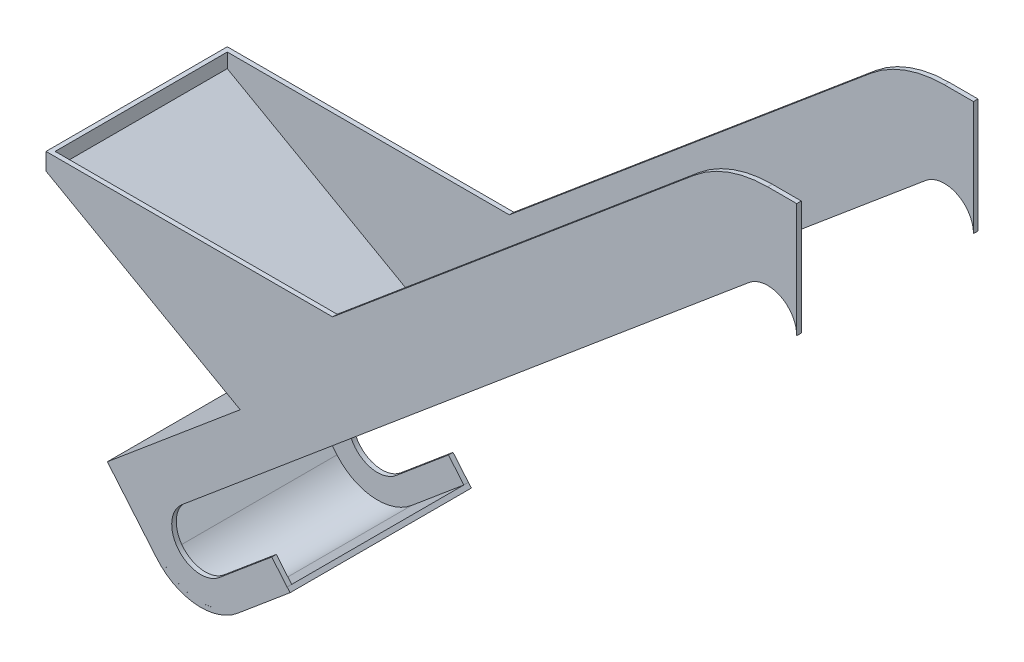
SolidWorks part; units mm, degrees
ref_plane "前视基准面" through (0, 0, 0) normal (0, 0, 1) x (1, 0, 0)
ref_plane "上视基准面" through (0, 0, 0) normal (0, 1, 0) x (1, 0, 0)
ref_plane "右视基准面" through (0, 0, 0) normal (1, 0, 0) x (0, 0, -1)
sketch "草图4" plane through (0, 0, 0) normal (0, 0, 1) x (1, 0, 0)
  line L0 (420.9878, 562.8861) -> (471.9878, 562.8861)
  line L1 (-659.0341, -373.4463) -> (-501.8251, -241.5173)
  line L2 (-659.0341, -373.4463) -> (-730.1522, -433.1283)
  line L3 (-730.1522, -433.1283) -> (-645.9414, -533.4754)
  line L4 (471.9878, 361.8861) -> (471.9878, 562.8861)
  line L7 (-542.039, -512.8599) -> (-450.118, -435.7202)
  line L8 (-423.1191, -467.8926) -> (-515.0187, -545.0143)
  line L9 (-659.0341, -373.4463) -> (336.777, 462.2332) construction
  line L10 (-607.6077, -434.727) -> (388.2035, 400.9525)
  line L11 (-450.118, -435.7202) -> (-423.1191, -467.8926)
  line L12 (-343.1983, -17.0157) -> (291.7789, 515.8538)
  line L14 (-846.6236, -17.0157) -> (-846.6236, -47.0157)
  line L15 (-846.6236, -17.0157) -> (-343.1983, -17.0157)
  line L16 (-846.6236, -47.0157) -> (-501.8251, -241.5173)
  arc A3 (-542.039, -512.8599) -> (-607.6077, -434.727) centre (-574.8233, -473.7934) cw
  arc A4 (388.2035, 400.9525) -> (471.9878, 361.8861) centre (420.9878, 361.8861) cw
  arc A5 (-515.0187, -545.0143) -> (-645.9414, -533.4754) centre (-574.7026, -473.6922) cw
  arc A7 (291.7789, 515.8538) -> (420.9878, 562.8861) centre (420.9878, 361.8861) cw
  point P33 (471.9878, 562.8861)
  dimension "D3" = 42
  dimension "D1" = 150
  dimension "D2" = 80
extrude "凸台-拉伸1" add sketch "草图4" along normal mid plane 8
pattern_linear "阵列(线性)1" count 2 spacing 310.4 along (0, 0, 1) of bodies 101
sketch "草图7" plane through (-224.4912, -397.962, 0) normal (-0.4913, -0.871, 0) x (0.871, -0.4913, 0)
  line L4 (-714.2913, 314.4) -> (-318.4164, 314.4)
  line L6 (-318.4164, 314.4) -> (-318.4164, -4)
  line L8 (-714.2913, 314.4) -> (-714.2913, -4)
  line L9 (-714.2913, -4) -> (-318.4164, -4)
extrude "凸台-拉伸2" add sketch "草图7" against normal blind 8
sketch "草图8" plane through (-846.6236, 0, 0) normal (-1, 0, 0) x (0, 0, 1)
  line L0 (-4, -47.0157) -> (314.4, -47.0157)
  line L1 (314.4, -47.0157) -> (314.4, -17.0157)
  line L2 (314.4, -17.0157) -> (-4, -17.0157)
  line L3 (-4, -17.0157) -> (-4, -47.0157)
extrude "凸台-拉伸3" add sketch "草图8" against normal blind 8
sketch "草图9" plane through (-88.4432, 105.3906, 0) normal (-0.6428, 0.766, 0) x (0.766, 0.6428, 0)
  line L0 (-837.7309, 4) -> (-837.7309, -314.4)
  line L1 (-837.7309, -314.4) -> (-539.657, -314.4)
  line L2 (-539.657, -314.4) -> (-539.657, 4)
  line L3 (-539.657, 4) -> (-837.7309, 4)
extrude "凸台-拉伸4" add sketch "草图9" along normal mid plane 8
sketch "草图10" plane through (0, 0, 314.4) normal (0, 0, 1) x (1, 0, 0)
  line L0 (-732.7235, -430.0642) -> (-645.9414, -533.4754)
  line L2 (-423.1191, -467.8926) -> (-515.0187, -545.0143)
  line L3 (-509.8761, -551.1424) -> (-417.8026, -473.8748)
  line L4 (-417.8026, -473.8748) -> (-423.1191, -467.8926)
  line L5 (-732.7235, -430.0642) -> (-738.8516, -435.2069)
  line L6 (-738.8516, -435.2069) -> (-652.0766, -538.6095)
  arc A0 (-515.0187, -545.0143) -> (-645.9414, -533.4754) centre (-574.7187, -473.8748) cw
  arc A1 (-509.8761, -551.1424) -> (-652.0766, -538.6095) centre (-574.7187, -473.8748) cw
  dimension "D1" = 8
extrude "凸台-拉伸5" add sketch "草图10" against normal blind 318.4
